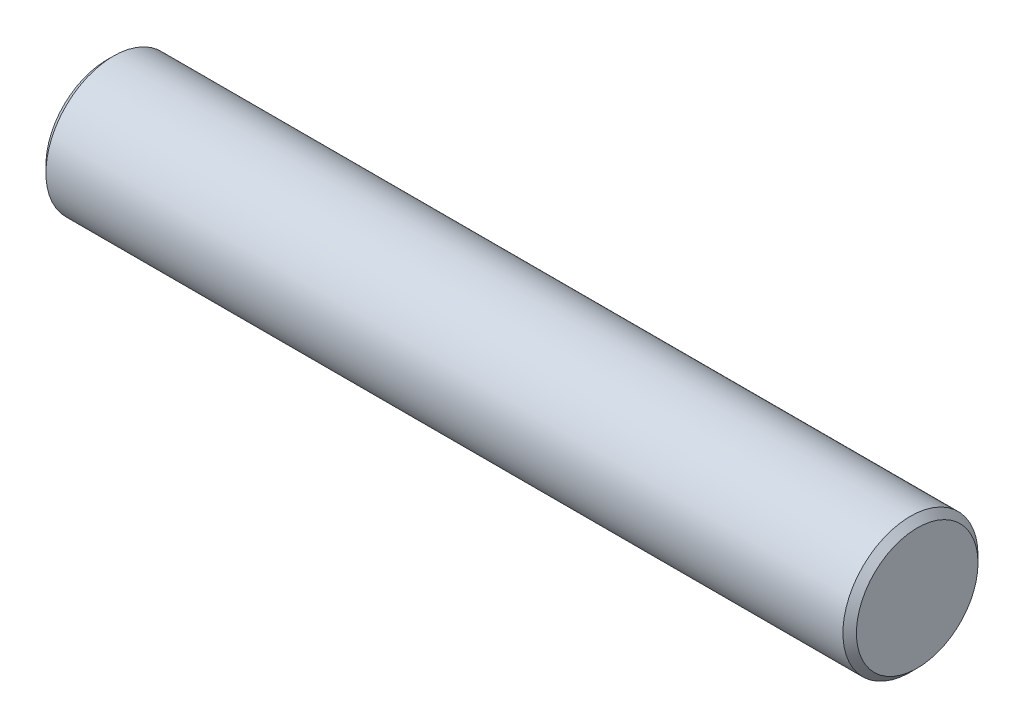
SolidWorks part; units mm, degrees
ref_plane "Front Plane" through (0, 0, 0) normal (0, 0, 1) x (1, 0, 0)
ref_plane "Top Plane" through (0, 0, 0) normal (0, 1, 0) x (1, 0, 0)
ref_plane "Right Plane" through (0, 0, 0) normal (1, 0, 0) x (0, 0, -1)
sketch "Sketch2" plane through (0, 0, 0) normal (1, 0, 0) x (0, 0, -1)
  circle A0 centre (0, 0) radius 1
  dimension "D1" = 2
extrude "Boss-Extrude1" add sketch "Sketch2" along normal mid plane 12
chamfer "Chamfer1" distance 0.1 angle 45 2 edges at (6, 0, -1) (-6, 0, -1)
